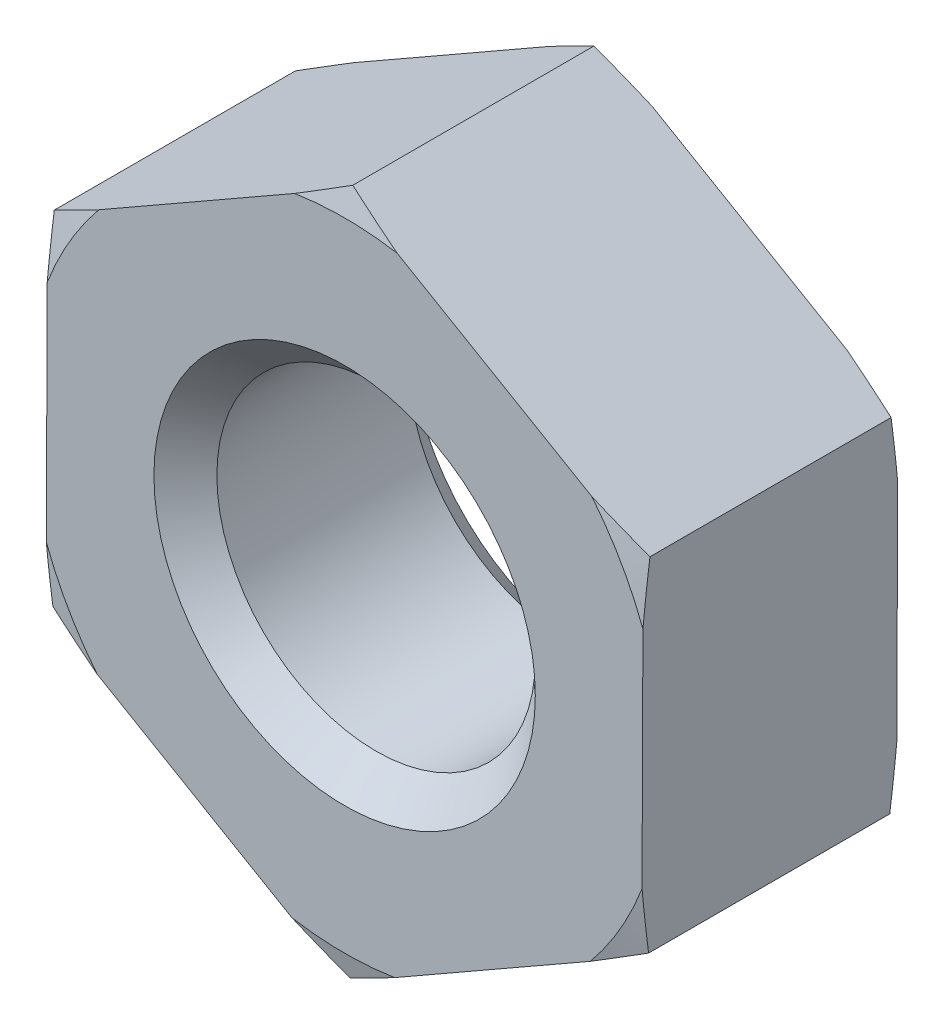
SolidWorks part; units mm, degrees
extrude "基体-拉伸" add sketch "草图1" along normal blind 1.6
sketch "草图1" plane through (0, 0, 0) normal (0, 0, 1) x (1, 0, 0)
  line L0 (-26.8088, 0) -> (37.1748, 0) construction
  line L1 (0, 25.0215) -> (0, -25.0215) construction
  line L3 (0.0085, 2.16) -> (-1.8664, 1.0873)
  line L4 (-1.8664, 1.0873) -> (-1.8748, -1.0726)
  line L5 (-1.8748, -1.0726) -> (-0.0085, -2.16)
  line L6 (-0.0085, -2.16) -> (1.8664, -1.0873)
  line L7 (1.8664, -1.0873) -> (1.8748, 1.0726)
  line L8 (1.8748, 1.0726) -> (0.0085, 2.16)
  circle A0 centre (0, 0) radius 1.8706 construction
  circle A1 centre (0, 0) radius 1
  dimension "D" = 2
  dimension "e" = 4.32
cosmetic thread "装饰螺纹线1"
chamfer "倒角1" distance 0.1976 angle 45 2 edges at (1, 0, 0) (1, 0, 1.6)
ref_plane "基准面1" through (0, 0, 0) normal (0, 0, 1) x (1, 0, 0)
ref_plane "基准面2" through (0, 0, 0) normal (0, 1, 0) x (1, 0, 0)
ref_plane "基准面3" through (0, 0, 0) normal (1, 0, 0) x (0, 0, -1)
sketch "尺寸草图" plane through (0, 0, 0) normal (0, 0, 1) x (1, 0, 0)
  line L0 (0, 0) -> (35.1249, 0)
  line L1 (35.1249, 0) -> (37.4249, 0)
  line L2 (37.4249, 0) -> (40.5249, 0)
  line L3 (-1.9048, 0) -> (0, 0)
  point P3 (2, 0)
  point P4 (1.5, 0)
  point P5 (4.32, 0)
  point P6 (1.6, 0)
  point P7 (6.4, 0)
  point P8 (4, 0)
  dimension "D" = 2
  dimension "e" = 4.32
  dimension "P" = 1.5
  dimension "m" = 1.6
  dimension "mw" = 6.4
  dimension "s" = 4
  dimension "da" = 2.3
  dimension "dw" = 3.1
  dimension "D1" = 1.9048
sketch "草图2" plane through (0, 0, 0) normal (0, 0, -1) x (-1, 0, 0)
  circle A0 centre (0, 0) radius 2
  circle A1 centre (0, 0) radius 1 construction
  dimension "s" = 4
extrude "切除-拉伸1" cut sketch "草图2" against normal through all draft 75 flip side to cut
sketch "草图3" plane through (0, 0, 1.6) normal (0, 0, 1) x (1, 0, 0)
  circle A0 centre (0, 0) radius 2
  dimension "D1" = 4
extrude "切除-拉伸2" cut sketch "草图3" against normal through all draft 75 flip side to cut
equation "\"e@草图1\" = \"e@尺寸草图\""
equation "\"D1@尺寸草图\" = \"D@尺寸草图\" / 1.05"
equation "\"D@草图1\" = \"D@尺寸草图\""
equation "\"m@基体-拉伸\" = \"m@尺寸草图\""
equation "\"D1@草图3\" = \"s@尺寸草图\""
equation "\"s@草图2\" = \"s@尺寸草图\""
equation "\"D2@装饰螺纹线1\" =\"D@尺寸草图\""
equation "\"D1@倒角1\" =  ( \"da@尺寸草图\" - \"D1@尺寸草图\" )  / 2"
